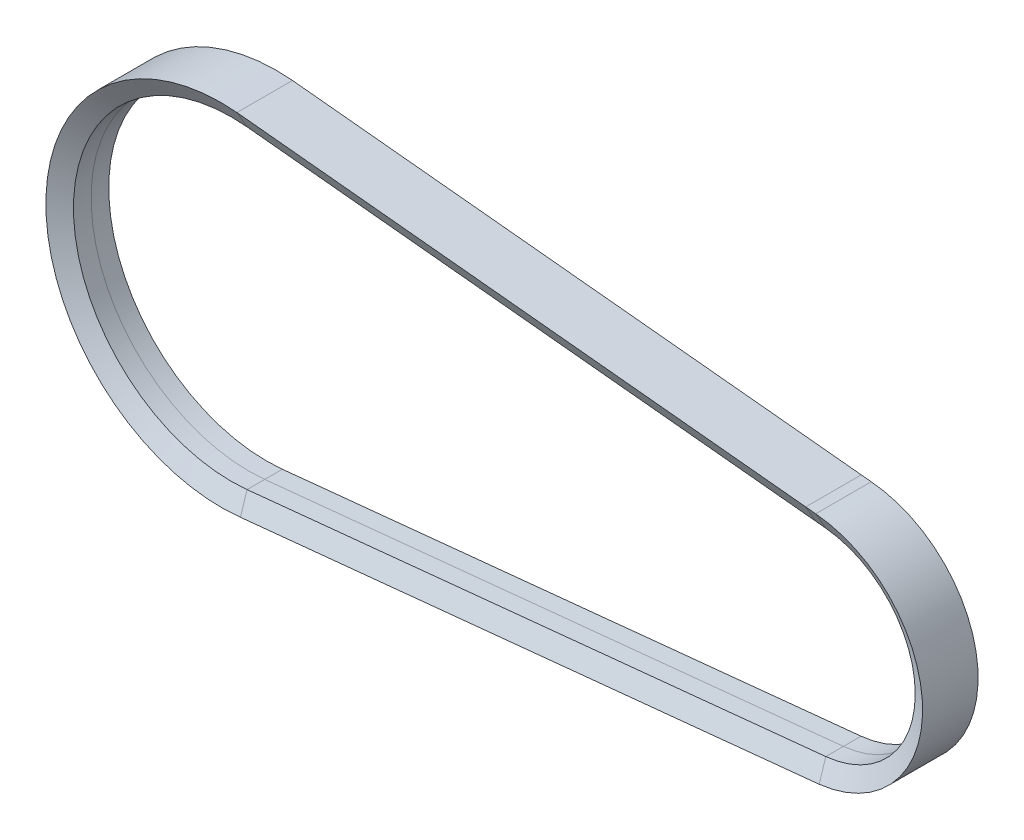
SolidWorks part; units mm, degrees
ref_plane "Front Plane" through (0, 0, 0) normal (0, 0, 1) x (1, 0, 0)
ref_plane "Top Plane" through (0, 0, 0) normal (0, 1, 0) x (1, 0, 0)
ref_plane "Right Plane" through (0, 0, 0) normal (1, 0, 0) x (0, 0, -1)
sketch "Sketch2" plane through (0, 0, 0) normal (0, 0, 1) x (1, 0, 0)
  line L0 (0, 0) -> (1, 0) construction
  line L1 (0, 0) -> (0, 1) construction
  line L2 (3.4, -33.8296) -> (-194.6, -53.7293)
  line L3 (-194.6, 53.7293) -> (3.4, 33.8296)
  arc A0 (3.4, 33.8296) -> (3.4, -33.8296) centre (0, 0) cw
  arc A1 (-194.6, -53.7293) -> (-194.6, 53.7293) centre (-200, 0) cw
sketch "Sketch4" plane through (0, 0, 0) normal (1, 0, 0) x (0, 0, -1)
  line L0 (0, 34.1713) -> (6.035, 34.1713)
  line L1 (6.035, 34.1713) -> (9.4991, 40.1713)
  line L2 (9.4991, 40.1713) -> (-9.4991, 40.1713)
  line L3 (-9.4991, 40.1713) -> (-6.035, 34.1713)
  line L4 (-6.035, 34.1713) -> (0, 34.1713)
  line L5 (0, 54) -> (0, -54) construction
  point P2 (-5.1913, 36.1831)
  point P6 (0, 43.6819)
  point P9 (0, 35.8398)
  point P12 (0, 0)
  dimension "D1" = 60
  dimension "D2" = 60
  dimension "D3" = 12.07
  dimension "D4" = 6
sweep "Sweep1" add profiles "Sketch4" path "Sketch2"
